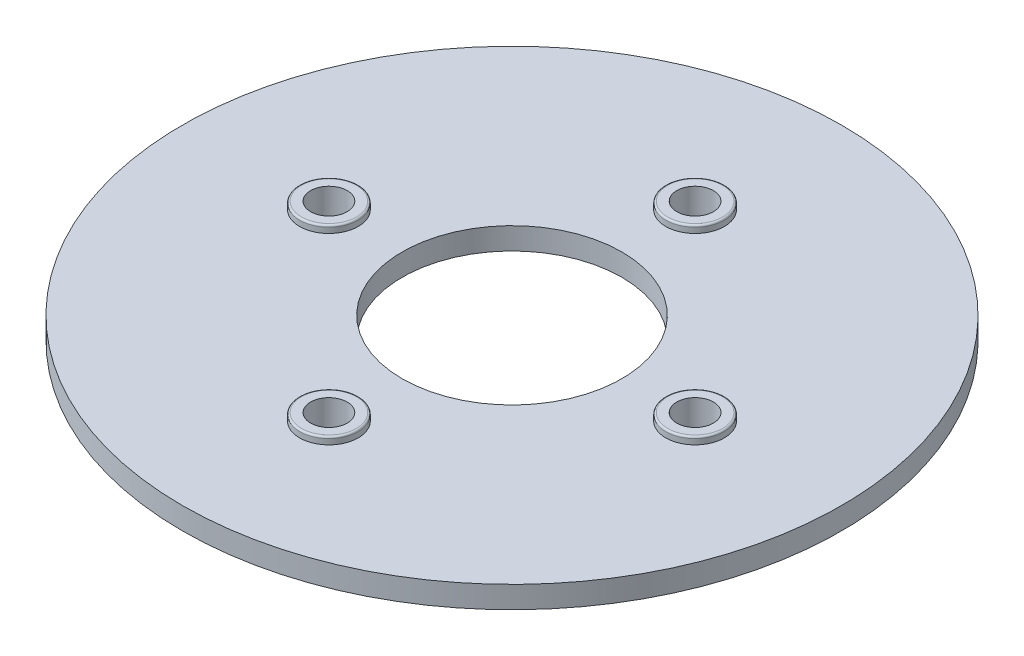
SolidWorks part; units mm, degrees
ref_plane "Front Plane" through (0, 0, 0) normal (0, 0, 1) x (1, 0, 0)
ref_plane "Top Plane" through (0, 0, 0) normal (0, 1, 0) x (1, 0, 0)
ref_plane "Right Plane" through (0, 0, 0) normal (1, 0, 0) x (0, 0, -1)
sketch "Sketch1" plane through (0, 0, 0) normal (0, 1, 0) x (1, 0, 0)
  circle A0 centre (0, 0) radius 45
  circle A1 centre (0, 0) radius 15
  circle A2 centre (0, 0) radius 25
  circle A3 centre (0, 25) radius 2.5
  circle A4 centre (25, 0) radius 2.5
  circle A5 centre (0, -25) radius 2.5
  circle A6 centre (-25, 0) radius 2.5
  point P16 (0, 0)
  dimension "D1" = 90
  dimension "D2" = 30
  dimension "D3" = 50
  dimension "D4" = 5
  dimension "D5" = 4
extrude "Boss-Extrude1" add sketch "Sketch1" along normal blind 3 contours A0 A6 A2 A3 A4 A5 | A6 A2 A5 A4 A3 A1
sketch "Sketch2" plane through (0, 3, 0) normal (0, 1, 0) x (1, 0, 0)
  circle A0 centre (0, 0) radius 25
  circle A1 centre (0, 25) radius 4
  circle A2 centre (0, 25) radius 2.5
  circle A3 centre (25, 0) radius 2.5
  circle A4 centre (25, 0) radius 4
  circle A5 centre (0, -25) radius 2.5
  circle A6 centre (0, -25) radius 4
  circle A7 centre (-25, 0) radius 2.5
  circle A8 centre (-25, 0) radius 4
  point P19 (0, 0)
  circle M1 centre (-25, 0) radius 2.5
  circle M2 centre (0, 25) radius 2.5
  circle M3 centre (25, 0) radius 2.5
  circle M4 centre (0, -25) radius 2.5
  dimension "D1" = 8
  dimension "D2" = 5
  dimension "D3" = 4
extrude "Boss-Extrude2" add sketch "Sketch2" along normal blind 1 contours A0 A8 M1 | A0 A8 M1 | A0 A6 M4 | A0 A6 M4 | A0 A4 M3 | A0 A4 M3 | A0 A1 M2 | A0 A1 M2
fillet "Fillet1" radius 0.25 4 edges at (25, 4, 4) (0, 4, 29) (-25, 4, 4) (0, 4, -21)
